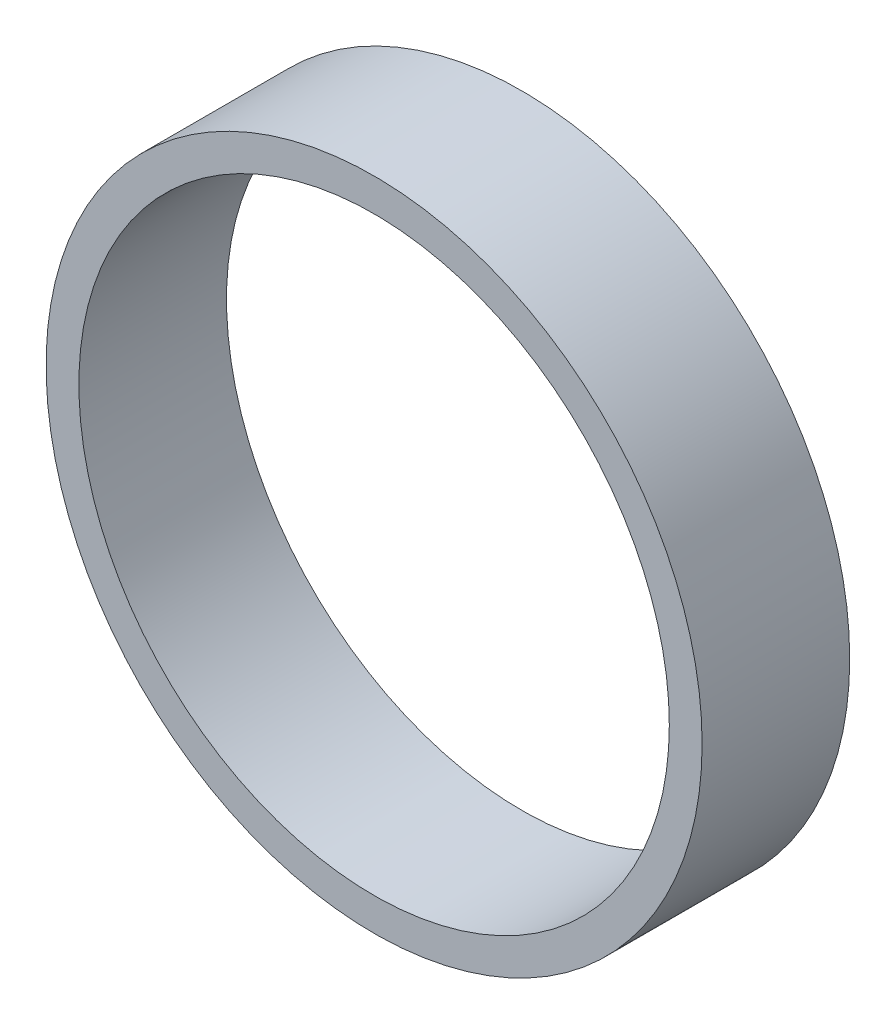
SolidWorks part; units mm, degrees
ref_plane "Front Plane" through (0, 0, 0) normal (0, 0, 1) x (1, 0, 0)
ref_plane "Top Plane" through (0, 0, 0) normal (0, 1, 0) x (1, 0, 0)
ref_plane "Right Plane" through (0, 0, 0) normal (1, 0, 0) x (0, 0, -1)
sketch "Sketch1" plane through (0, 0, 0) normal (0, 0, 1) x (1, 0, 0)
  circle A0 centre (0, 0) radius 25.4
  dimension "D1" = 50.8
extrude "Boss-Extrude1" add sketch "Sketch1" along normal blind 11.43
sketch "Sketch2" plane through (0, 0, 11.43) normal (0, 0, 1) x (1, 0, 0)
  circle A0 centre (0, 0) radius 22.86
  circle A1 centre (0, 0) radius 25.4 construction
  dimension "D1" = 2.54
extrude "Cut-Extrude1" cut sketch "Sketch2" against normal through all
